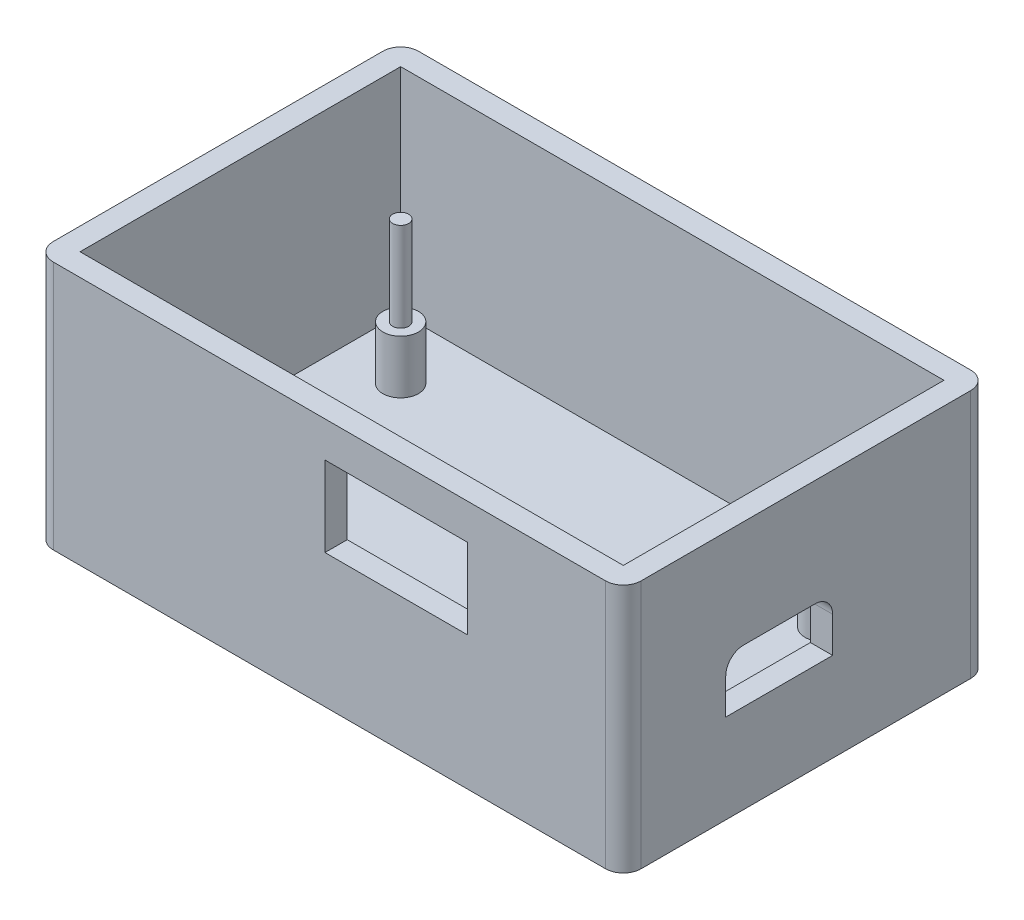
SolidWorks part; units mm, degrees
ref_plane "Front Plane" through (0, 0, 0) normal (0, 0, 1) x (1, 0, 0)
ref_plane "Top Plane" through (0, 0, 0) normal (0, 1, 0) x (1, 0, 0)
ref_plane "Right Plane" through (0, 0, 0) normal (1, 0, 0) x (0, 0, -1)
sketch "Sketch1" plane through (0, 0, 0) normal (0, 1, 0) x (1, 0, 0)
  line L0 (-7.5, -7.5) -> (-7.5, 33.5)
  line L1 (0, 0) -> (51, 0) construction
  line L2 (0, 0) -> (0, 26) construction
  line L3 (0, 26) -> (51, 26) construction
  line L4 (51, 0) -> (51, 26) construction
  line L5 (-7.5, 33.5) -> (58.5, 33.5)
  line L6 (58.5, -7.5) -> (58.5, 33.5)
  line L7 (-7.5, -7.5) -> (58.5, -7.5)
  line L8 (25.5, 33.5) -> (25.5, -7.5) construction
  line L9 (-7.5, 13) -> (58.5, 13) construction
  dimension "D1" = 51
  dimension "D2" = 26
  dimension "D3" = 7.5
extrude "Boss-Extrude1" add sketch "Sketch1" along normal blind 4
sketch "Sketch2" plane through (0, 4, 0) normal (0, 1, 0) x (1, 0, 0)
  line L0 (0, 13) -> (51, 13) construction
  line L1 (25.5, 26) -> (25.5, 0) construction
  line L8 (0, 26) -> (0, 0)
  line L9 (51, 26) -> (0, 26)
  line L10 (51, 0) -> (51, 26)
  line L11 (0, 0) -> (51, 0)
  line L12 (0, 26) -> (0, 0) construction
  line L13 (51, 26) -> (0, 26) construction
  line L14 (51, 0) -> (51, 26) construction
  line L15 (0, 0) -> (51, 0) construction
  circle A4 centre (1.8, 24.2) radius 0.9
  circle A5 centre (1.8, 1.8) radius 0.9
  circle A6 centre (49.2, 1.8) radius 0.9
  circle A7 centre (49.2, 24.2) radius 0.9
  dimension "D2" = 1.8
  dimension "D3" = 1.8
  dimension "D4" = 1.8
  dimension "D1" = 7.5
sketch "Sketch3" plane through (0, 4, 0) normal (0, 1, 0) x (1, 0, 0)
  line L0 (58.5, -7.5) -> (58.5, 33.5) construction
  line L1 (-7.5, -7.5) -> (58.5, -7.5) construction
  line L2 (58.5, 33.5) -> (-7.5, 33.5) construction
  line L3 (-7.5, 33.5) -> (-7.5, -7.5) construction
  line L4 (58.5, -7.5) -> (58.5, 33.5)
  line L5 (-7.5, -7.5) -> (58.5, -7.5)
  line L6 (58.5, 33.5) -> (-7.5, 33.5)
  line L7 (-7.5, 33.5) -> (-7.5, -7.5)
  line L8 (56, -5) -> (56, 31)
  line L9 (56, 31) -> (-5, 31)
  line L10 (-5, 31) -> (-5, -5)
  line L11 (-5, -5) -> (56, -5)
  dimension "D1" = 2.5
extrude "Boss-Extrude3" add sketch "Sketch3" along normal blind 24
extrude "Boss-Extrude4" add sketch "Sketch2" along normal blind 16
sketch "Sketch4" plane through (0, 4, 0) normal (0, 1, 0) x (1, 0, 0)
  line L0 (25.5, 31) -> (25.5, -5) construction
  line L1 (56, 31) -> (-5, 31) construction
  line L2 (-5, -5) -> (56, -5) construction
  line L3 (-5, 13) -> (56, 13) construction
  line L4 (-5, 31) -> (-5, -5) construction
  line L5 (56, -5) -> (56, 31) construction
  circle A0 centre (1.8, 24.2) radius 2
  circle A1 centre (1.8, 1.8) radius 2
  circle A2 centre (49.2, 1.8) radius 2
  circle A3 centre (49.2, 24.2) radius 2
  dimension "D1" = 4
extrude "Boss-Extrude5" add sketch "Sketch4" along normal blind 6
sketch "Sketch5" plane through (58.5, 0, 0) normal (1, 0, 0) x (0, 0, -1)
  line L1 (-5, 28) -> (-5, 4) construction
  line L7 (4, 16) -> (16, 16)
  line L8 (4, 16) -> (4, 10)
  line L9 (4, 10) -> (16, 10)
  line L10 (16, 16) -> (16, 10)
  line L11 (-5, 4) -> (31, 4) construction
  line L12 (-5, 28) -> (-5, 4) construction
  line L13 (-5, 4) -> (31, 4) construction
  dimension "D1" = 6
  dimension "D2" = 12
  dimension "D3" = 6
  dimension "D4" = 9
extrude "Cut-Extrude1" cut sketch "Sketch5" against normal blind 6
fillet "Fillet2" radius 2 4 edges at (-7.5, 14, 7.5) (-7.5, 14, -33.5) (58.5, 14, -33.5) (58.5, 14, 7.5)
fillet "Fillet3" radius 2 2 edges at (57.25, 16, -4) (57.25, 16, -16)
sketch "Sketch6" plane through (0, 0, 7.5) normal (0, 0, 1) x (1, 0, 0)
  line L0 (-5, 4) -> (56, 4) construction
  line L1 (56, 28) -> (56, 4) construction
  line L2 (-5, 4) -> (56, 4) construction
  line L3 (56, 28) -> (56, 4) construction
  line L5 (25, 24) -> (41, 24)
  line L6 (25, 24) -> (25, 15)
  line L7 (25, 15) -> (41, 15)
  line L8 (41, 24) -> (41, 15)
  dimension "D1" = 16
  dimension "D2" = 9
  dimension "D3" = 15
  dimension "D4" = 11
extrude "Cut-Extrude2" cut sketch "Sketch6" against normal blind 6 contours L7 L8 L5 L6
